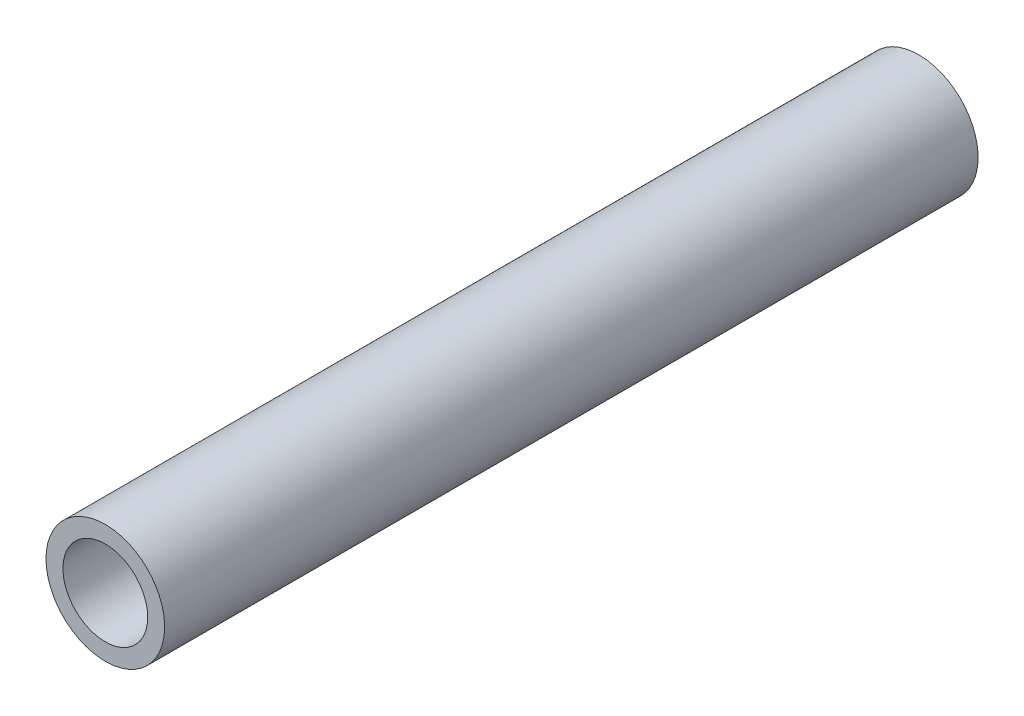
SolidWorks part; units mm, degrees
ref_plane "Front Plane" through (0, 0, 0) normal (0, 0, 1) x (1, 0, 0)
ref_plane "Top Plane" through (0, 0, 0) normal (0, 1, 0) x (1, 0, 0)
ref_plane "Right Plane" through (0, 0, 0) normal (1, 0, 0) x (0, 0, -1)
sketch "Sketch2" plane through (0, 0, 0) normal (0, 0, 1) x (1, 0, 0)
  circle A0 centre (0, 0) radius 8.89
  dimension "D1" = 17.78
extrude "Boss-Extrude1" add sketch "Sketch2" along normal blind 121.92
sketch "Sketch3" plane through (0, 0, 121.92) normal (0, 0, 1) x (1, 0, 0)
  circle A0 centre (0, 0) radius 6.35
  dimension "D1" = 12.7
extrude "Cut-Extrude1" cut sketch "Sketch3" against normal through all
equation "\"FoamCore\" = \".2\""
equation "\"MDF\" = \".2\""
equation "\"GMaterial\"= \".2\""
equation "\"BaseWidth\" = \"10in\""
equation "\"BaseLength\" = \"8in\""
equation "\"BallDiameter\" = \"1.57in\""
equation "\"BaseGap\" = \"4in\""
equation "\"D1@Boss-Extrude1\"=\"BaseGap\" + (4*\"GMaterial\")"
equation "\"PVCMountDiameter\" = \"0.5in\""
equation "\"PVCMountDistanceToEdge\" = \"0.5\""
equation "\"FunnelTopDiameter\" = \"8in\""
equation "\"FunnelTopDepth\" = \"1.5in\""
equation "\"BallGap\" = \"0.1in\""
equation "\"FunnelLength\" = 6in"
equation "\"FunnelMaterial\" = 0.1in"
equation "\"D1@Sketch2\"=\"PVCMountDiameter\" + \"GMaterial\""
equation "\"D1@Sketch3\"=\"PVCMountDiameter\""
